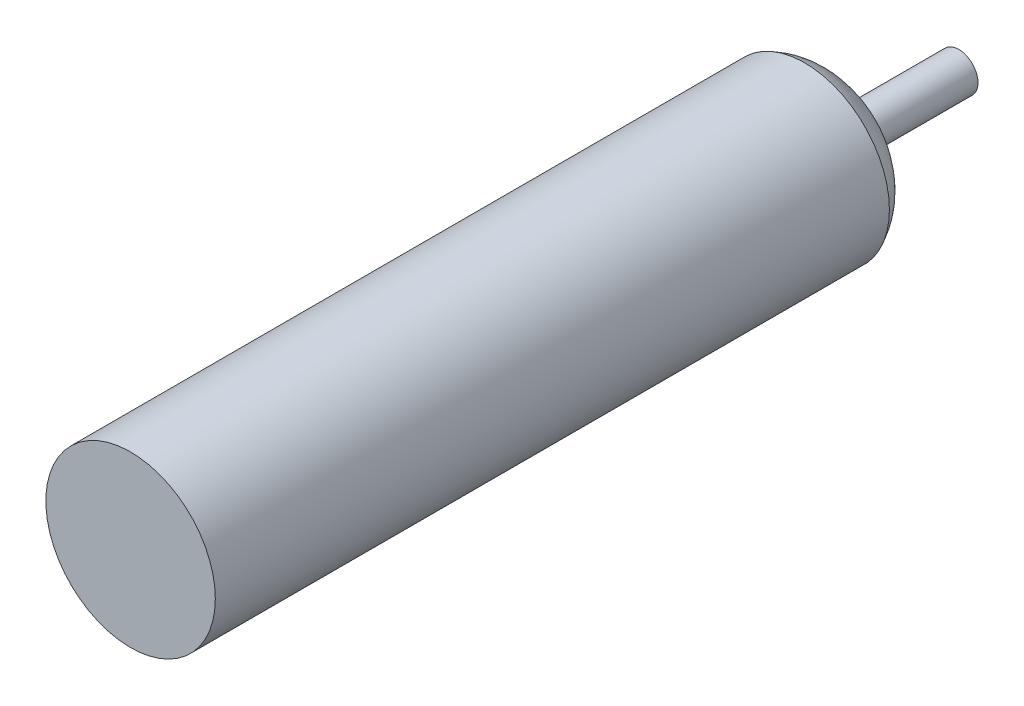
SolidWorks part; units mm, degrees
ref_plane "Front Plane" through (0, 0, 0) normal (0, 0, 1) x (1, 0, 0)
ref_plane "Top Plane" through (0, 0, 0) normal (0, 1, 0) x (1, 0, 0)
ref_plane "Right Plane" through (0, 0, 0) normal (1, 0, 0) x (0, 0, -1)
sketch "Sketch1" plane through (0, 0, 0) normal (0, 0, 1) x (1, 0, 0)
  circle A0 centre (0, 0) radius 55.88
  dimension "D1" = 111.76
extrude "Boss-Extrude1" add sketch "Sketch1" along normal blind 444.5
sketch "Sketch3" plane through (0, 0, 0) normal (1, 0, 0) x (0, 0, -1)
  line L0 (0, 0) -> (25.4, 0) construction
  line L1 (25.4, -12.7) -> (25.4, 0)
  line L6 (25.4, 0) -> (0, 0)
  line L7 (0, 0) -> (0, -55.88)
  arc A0 (25.4, -12.7) -> (0, -55.88) centre (-18.9505, -15.672) cw
  dimension "D3" = 44.45
  dimension "D1" = 12.7
  dimension "D2" = 25.4
revolve "Revolve1" add sketch "Sketch3" angle 360 about L0
sketch "Sketch4" plane through (0, 0, -25.4) normal (0, 0, -1) x (-1, 0, 0)
  circle A0 centre (0, 0) radius 12.7
  dimension "D1" = 25.4
extrude "Boss-Extrude3" add sketch "Sketch4" along normal blind 76.2
